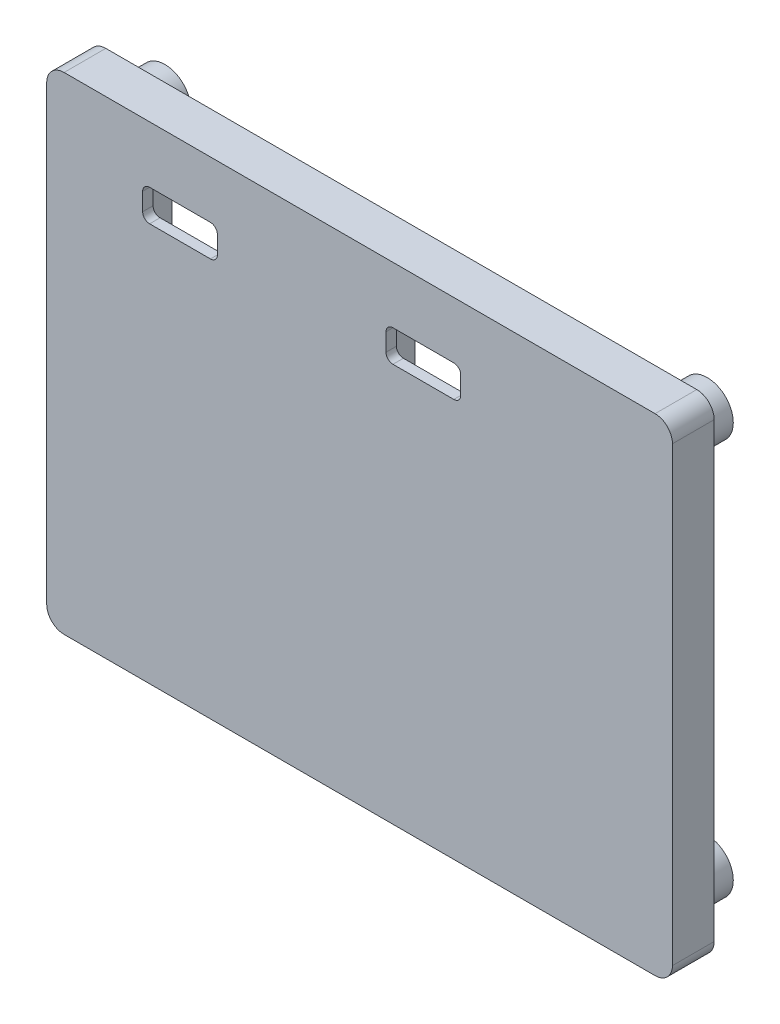
SolidWorks part; units mm, degrees
ref_plane "Front Plane" through (0, 0, 0) normal (0, 0, 1) x (1, 0, 0)
ref_plane "Top Plane" through (0, 0, 0) normal (0, 1, 0) x (1, 0, 0)
ref_plane "Right Plane" through (0, 0, 0) normal (1, 0, 0) x (0, 0, -1)
sketch "Sketch1" plane through (0, 0, 0) normal (0, 0, 1) x (1, 0, 0)
  line L1 (0, 0) -> (180, 0)
  line L2 (0, 0) -> (0, -140)
  line L3 (0, -140) -> (180, -140)
  line L4 (180, 0) -> (180, -140)
  dimension "D1" = 180
  dimension "D2" = 140
extrude "Boss-Extrude1" add sketch "Sketch1" along normal blind 12
sketch "Sketch2" plane through (0, 0, 0) normal (0, 0, -1) x (-1, 0, 0)
  line L0 (-90, -1000) -> (-90, 49000) construction
  line L1 (-156, -14) -> (-94, -14)
  line L2 (-156, -14) -> (-156, -126)
  line L3 (-156, -126) -> (-94, -126)
  line L4 (-94, -14) -> (-94, -126)
  line L5 (-86, -14) -> (-24, -14)
  line L6 (-86, -14) -> (-86, -126)
  line L7 (-86, -126) -> (-24, -126)
  line L8 (-24, -14) -> (-24, -126)
  line L9 (-180, 0) -> (0, 0) construction
  line L10 (-1140, -70) -> (48860, -70) construction
  line L11 (-180, -140) -> (-180, 0) construction
  point P13 (-90, 0)
  point P18 (-180, -70)
  dimension "D1" = 112
  dimension "D2" = 62
  dimension "D3" = 8
extrude "Cut-Extrude1" cut sketch "Sketch2" against normal blind 9
sketch "Sketch3" plane through (0, 0, 0) normal (0, 0, -1) x (-1, 0, 0)
  line L0 (-90, -1000) -> (-90, 49000) construction
  line L1 (-180, 0) -> (0, 0) construction
  line L2 (-1180, -70) -> (48820, -70) construction
  line L3 (-180, -140) -> (-180, 0) construction
  circle A0 centre (-168, -13) radius 7.5
  circle A1 centre (-12, -13) radius 7.5
  circle A2 centre (-12, -127) radius 7.5
  circle A3 centre (-168, -127) radius 7.5
  point P13 (-90, 0)
  point P18 (-180, -70)
  dimension "D1" = 15
  dimension "D2" = 78
  dimension "D3" = 57
extrude "Boss-Extrude2" add sketch "Sketch3" along normal blind 10
sketch "Sketch4" plane through (0, 0, 9) normal (0, 0, -1) x (-1, 0, 0)
  line L0 (-94, -14) -> (-156, -14) construction
  line L1 (-119.1, -16.3) -> (-97.6, -16.3)
  line L2 (-119.1, -16.3) -> (-119.1, -25.4)
  line L3 (-119.1, -25.4) -> (-97.6, -25.4)
  line L4 (-97.6, -16.3) -> (-97.6, -25.4)
  line L5 (-49.1, -16.3) -> (-27.6, -16.3)
  line L6 (-49.1, -16.3) -> (-49.1, -25.4)
  line L7 (-49.1, -25.4) -> (-27.6, -25.4)
  line L8 (-27.6, -16.3) -> (-27.6, -25.4)
  line L11 (-94, -126) -> (-94, -14) construction
  line L12 (-24, -126) -> (-24, -14) construction
  dimension "D1" = 2.3
  dimension "D2" = 3.6
  dimension "D3" = 9.1
  dimension "D4" = 21.5
  dimension "D5" = 3.6
extrude "Cut-Extrude2" cut sketch "Sketch4" against normal through all
fillet "Fillet4" radius 2 1 edges at (119.1, -16.3, 10.5)
fillet "Fillet5" radius 2 3 edges at (119.1, -25.4, 10.5) (97.6, -25.4, 10.5) (97.6, -16.3, 10.5)
fillet "Fillet6" radius 2 4 edges at (49.1, -16.3, 10.5) (49.1, -25.4, 10.5) (27.6, -25.4, 10.5) (27.6, -16.3, 10.5)
fillet "Fillet7" radius 5 4 edges at (180, -140, 6) (0, -140, 6) (0, 0, 6) (180, 0, 6)
